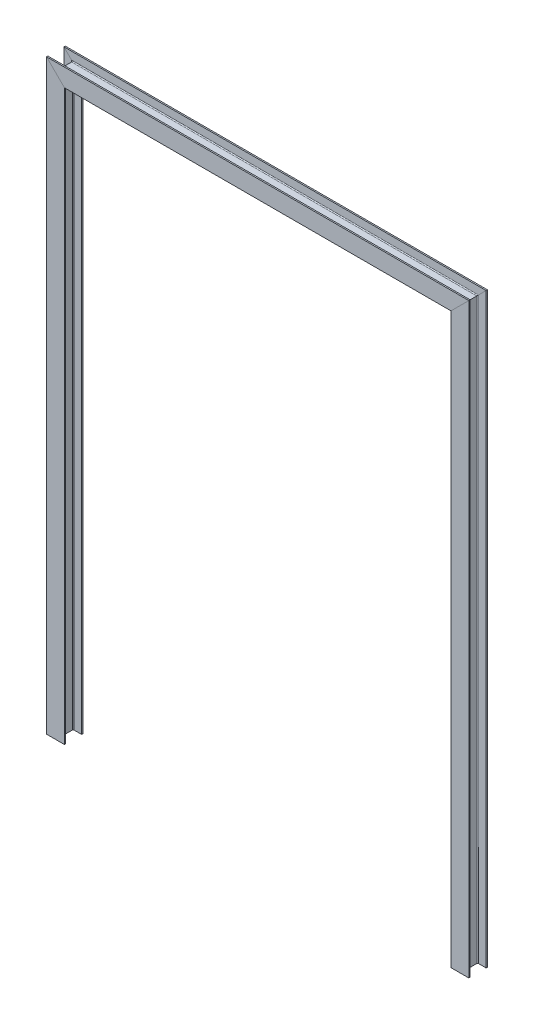
SolidWorks part; units mm, degrees
material "ASTM A36 Steel"
ref_plane "Front Plane" through (0, 0, 0) normal (0, 0, 1) x (1, 0, 0)
ref_plane "Top Plane" through (0, 0, 0) normal (0, 1, 0) x (1, 0, 0)
ref_plane "Right Plane" through (0, 0, 0) normal (1, 0, 0) x (0, 0, -1)
sketch "Sketch1" plane through (0, 0, 0) normal (0, 0, 1) x (1, 0, 0)
  line L0 (0, 0) -> (0, 10000)
  line L1 (0, 10000) -> (7000, 10000)
  line L2 (7000, 10000) -> (7000, 0)
  dimension "D1" = 10000
  dimension "D2" = 7000
other "W section W12X96(1)"
ref_plane "Plane1" through (0, 0, 0) normal (0, 1, 0) x (-1, 0, 0)
sketch "Sketch11" plane through (0, 0, 0) normal (0, 1, 0) x (-1, 0, 0)
  line L0 (-154.432, -161.417) -> (-154.432, -138.557)
  line L1 (-154.432, -138.557) -> (-22.225, -138.557)
  line L2 (-6.985, -123.317) -> (-6.985, 123.317)
  line L3 (-22.225, 138.557) -> (-154.432, 138.557)
  line L4 (-154.432, 138.557) -> (-154.432, 161.417)
  line L5 (-154.432, 161.417) -> (154.432, 161.417)
  line L6 (154.432, 161.417) -> (154.432, 138.557)
  line L7 (154.432, 138.557) -> (22.225, 138.557)
  line L8 (6.985, 123.317) -> (6.985, -123.317)
  line L9 (22.225, -138.557) -> (154.432, -138.557)
  line L10 (154.432, -138.557) -> (154.432, -161.417)
  line L11 (154.432, -161.417) -> (-154.432, -161.417)
  line L12 (0, 0) -> (0, 161.417) construction
  line L13 (-6.985, 0) -> (6.985, 0) construction
  arc A0 (-22.225, -138.557) -> (-6.985, -123.317) centre (-22.225, -123.317) ccw
  arc A1 (-6.985, 123.317) -> (-22.225, 138.557) centre (-22.225, 123.317) ccw
  arc A2 (22.225, 138.557) -> (6.985, 123.317) centre (22.225, 123.317) ccw
  arc A3 (6.985, -123.317) -> (22.225, -138.557) centre (22.225, -123.317) ccw
  point P23 (-154.432, 0)
  point P26 (0, -161.417)
  point P27 (154.432, 0)
  point P28 (0, 0)
  dimension "Ri" = 15.24
  dimension "D1" = 6.985
  dimension "D2" = 22.86
  dimension "Tw" = 13.97
  dimension "Bf" = 308.864
  dimension "Depth" = 322.834
  dimension "Tf" = 22.86
